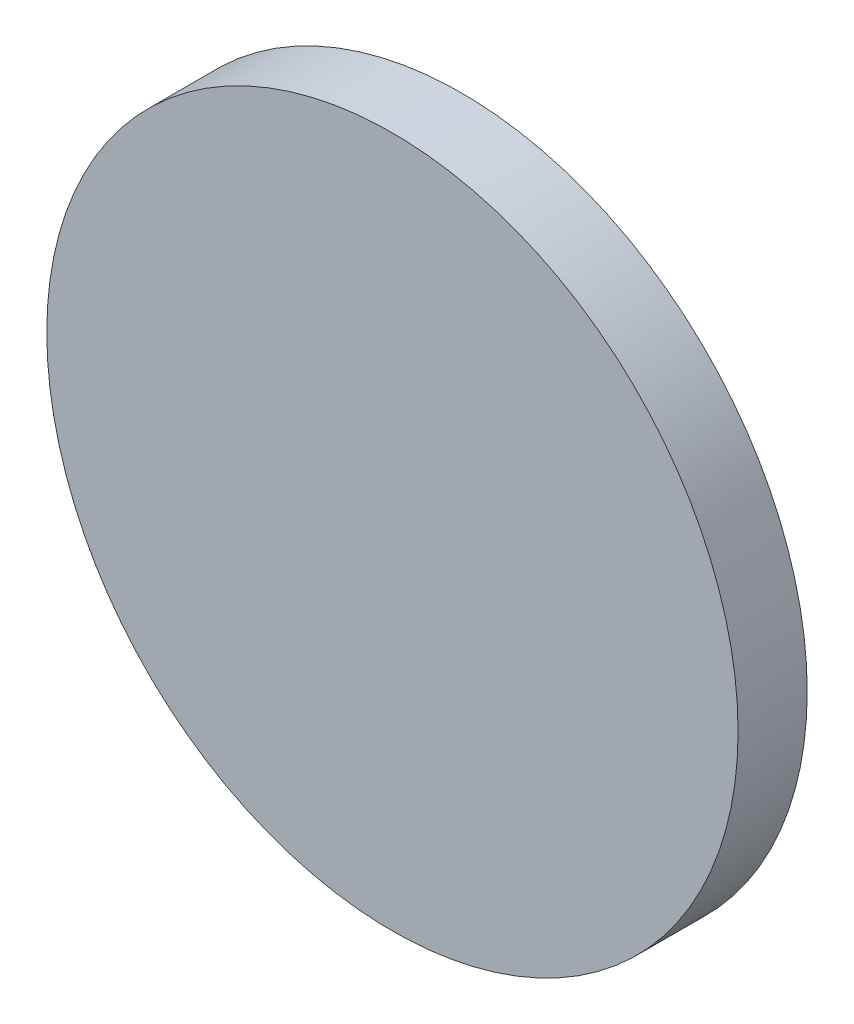
SolidWorks part; units mm, degrees
ref_plane "Plane1" through (0, 0, 0) normal (0, 0, 1) x (1, 0, 0)
ref_plane "Plane2" through (0, 0, 0) normal (0, 1, 0) x (1, 0, 0)
ref_plane "Plane3" through (0, 0, 0) normal (1, 0, 0) x (0, 0, -1)
sketch "Sketch1" plane through (0, 0, 0) normal (0, 0, 1) x (1, 0, 0)
  circle A0 centre (0, -179.95) radius 50 construction
  circle A1 centre (0, -179.95) radius 50
extrude "Base-Extrude" add sketch "Sketch1" against normal blind 10
